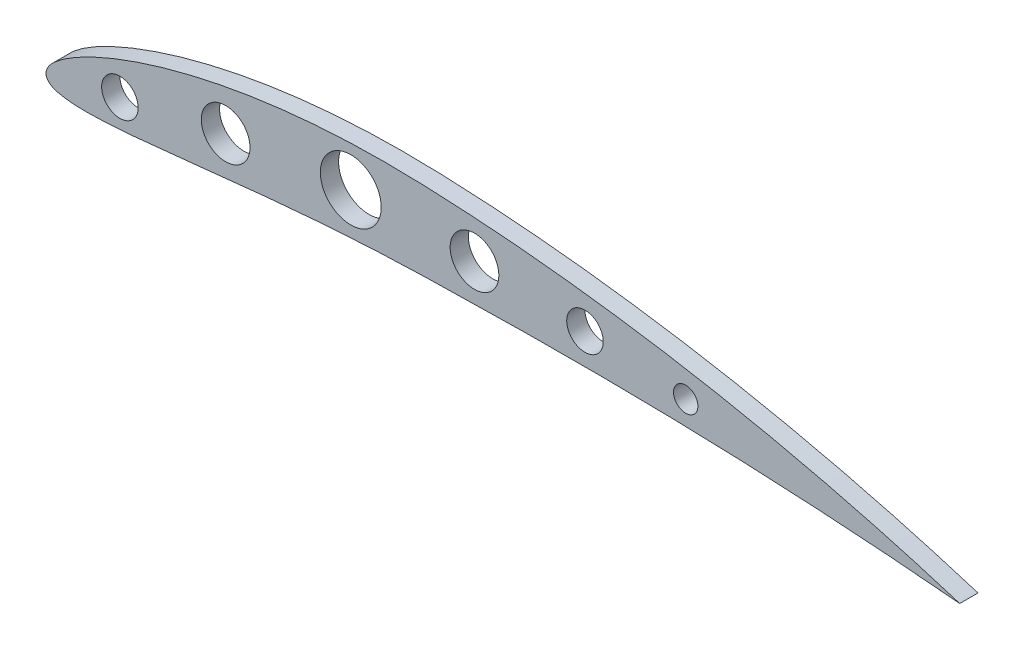
SolidWorks part; units mm, degrees
ref_plane "前基準面" through (0, 0, 0) normal (0, 0, 1) x (1, 0, 0)
ref_plane "上基準面" through (0, 0, 0) normal (0, 1, 0) x (1, 0, 0)
ref_plane "右基準面" through (0, 0, 0) normal (1, 0, 0) x (0, 0, -1)
curve "曲線1"
  spline degree 3 poles (149.1065, 0.1017, 0) (150.2196, -0.0437, 0) (149.135, 0.2489, 0) (148.2582, 0.5567, 0) (146.0923, 1.1965, 0) (143.4195, 1.9978, 0) (139.8974, 3.005, 0) (135.7082, 4.154, 0) (130.8404, 5.4202, 0) (125.3584, 6.7539, 0) (119.317, 8.1207, 0) (112.7765, 9.4732, 0) (105.8082, 10.7736, 0) (98.4853, 11.9821, 0) (90.8867, 13.0635, 0) (83.0963, 13.9879, 0) (75.2009, 14.7297, 0) (67.2867, 15.2583, 0) (59.4021, 15.5949, 0) (51.6307, 15.5985, 0) (44.0772, 15.1999, 0) (36.8788, 14.4542, 0) (30.1283, 13.3973, 0) (23.9108, 12.0837, 0) (18.3003, 10.5813, 0) (13.3638, 8.9553, 0) (9.152, 7.2857, 0) (5.7118, 5.628, 0) (3.0538, 4.0665, 0) (1.2116, 2.6133, 0) (0.0851, 1.3376, 0) (-0.1805, -0.0525, 0) (0.7965, -1.0705, 0) (2.413, -1.5314, 0) (4.6951, -1.8007, 0) (7.6882, -1.8133, 0) (11.3621, -1.6287, 0) (15.68, -1.2602, 0) (20.5924, -0.756, 0) (26.0492, -0.1597, 0) (31.9924, 0.4836, 0) (38.3682, 1.1208, 0) (45.1152, 1.6962, 0) (52.1754, 2.1713, 0) (59.5253, 2.4861, 0) (67.096, 2.6625, 0) (74.8069, 2.8196, 0) (82.5373, 2.8993, 0) (90.2002, 2.9074, 0) (97.7131, 2.8344, 0) (104.994, 2.6857, 0) (111.9628, 2.4672, 0) (118.5419, 2.1942, 0) (124.6567, 1.8797, 0) (130.2345, 1.5456, 0) (135.2162, 1.2065, 0) (139.5235, 0.8875, 0) (143.1607, 0.5942, 0) (145.9334, 0.3654, 0) (148.178, 0.1527, 0) (149.1065, 0.1017, 0) (150.2196, -0.0437, 0) (149.135, 0.2489, 0) knots -0.012269 -0.005489 -0.001366 0 0.001375 0.005484 0.012273 0.021682 0.033581 0.047831 0.064306 0.082777 0.103064 0.124929 0.148149 0.172445 0.197572 0.223269 0.249228 0.275186 0.300901 0.326463 0.351222 0.374906 0.39727 0.418072 0.43708 0.454093 0.46892 0.481392 0.491447 0.499024 0.504294 0.507922 0.51154 0.516781 0.524216 0.533992 0.546034 0.56022 0.576403 0.594371 0.613951 0.634917 0.657089 0.68023 0.704175 0.72909 0.754354 0.779668 0.80476 0.829359 0.853209 0.876041 0.897604 0.917662 0.93597 0.95231 0.966503 0.97835 0.987731 0.994511 0.998634 1 1.001375 1.005484 1.012273 periodic
sketch "草圖1" plane through (0, 0, 0) normal (0, 0, 1) x (1, 0, 0)
  circle A0 centre (50, 8.8348) radius 5
  circle A1 centre (105, 6.5566) radius 2
  circle A2 centre (29.4551, 6.5566) radius 4
  circle A3 centre (70.3168, 8.8348) radius 4
  circle A4 centre (88.4596, 7.9533) radius 3
  circle A5 centre (12.0879, 3.0405) radius 3
  spline S0 degree 3 poles (149.1065, 0.1017) (150.2196, -0.0437) (149.135, 0.2489) (148.2582, 0.5567) (146.0923, 1.1965) (143.4195, 1.9978) (139.8974, 3.005) (135.7082, 4.154) (130.8404, 5.4202) (125.3584, 6.7539) (119.317, 8.1207) (112.7765, 9.4732) (105.8082, 10.7736) (98.4853, 11.9821) (90.8867, 13.0635) (83.0963, 13.9879) (75.2009, 14.7297) (67.2867, 15.2583) (59.4021, 15.5949) (51.6307, 15.5985) (44.0772, 15.1999) (36.8788, 14.4542) (30.1283, 13.3973) (23.9108, 12.0837) (18.3003, 10.5813) (13.3638, 8.9553) (9.152, 7.2857) (5.7118, 5.628) (3.0538, 4.0665) (1.2116, 2.6133) (0.0851, 1.3376) (-0.1805, -0.0525) (0.7965, -1.0705) (2.413, -1.5314) (4.6951, -1.8007) (7.6882, -1.8133) (11.3621, -1.6287) (15.68, -1.2602) (20.5924, -0.756) (26.0492, -0.1597) (31.9924, 0.4836) (38.3682, 1.1208) (45.1152, 1.6962) (52.1754, 2.1713) (59.5253, 2.4861) (67.096, 2.6625) (74.8069, 2.8196) (82.5373, 2.8993) (90.2002, 2.9074) (97.7131, 2.8344) (104.994, 2.6857) (111.9628, 2.4672) (118.5419, 2.1942) (124.6567, 1.8797) (130.2345, 1.5456) (135.2162, 1.2065) (139.5235, 0.8875) (143.1607, 0.5942) (145.9334, 0.3654) (148.178, 0.1527) (149.1065, 0.1017) (150.2196, -0.0437) (149.135, 0.2489) knots -0.012269 -0.005489 -0.001366 0 0.001375 0.005484 0.012273 0.021682 0.033581 0.047831 0.064306 0.082777 0.103064 0.124929 0.148149 0.172445 0.197572 0.223269 0.249228 0.275186 0.300901 0.326463 0.351222 0.374906 0.39727 0.418072 0.43708 0.454093 0.46892 0.481392 0.491447 0.499024 0.504294 0.507922 0.51154 0.516781 0.524216 0.533992 0.546034 0.56022 0.576403 0.594371 0.613951 0.634917 0.657089 0.68023 0.704175 0.72909 0.754354 0.779668 0.80476 0.829359 0.853209 0.876041 0.897604 0.917662 0.93597 0.95231 0.966503 0.97835 0.987731 0.994511 0.998634 1 1.001375 1.005484 1.012273 only from (150, 0) to (150, 0) construction
  spline S1 degree 3 poles (149.1065, 0.1017) (150.2196, -0.0437) (149.135, 0.2489) (148.2582, 0.5567) (146.0923, 1.1965) (143.4195, 1.9978) (139.8974, 3.005) (135.7082, 4.154) (130.8404, 5.4202) (125.3584, 6.7539) (119.317, 8.1207) (112.7765, 9.4732) (105.8082, 10.7736) (98.4853, 11.9821) (90.8867, 13.0635) (83.0963, 13.9879) (75.2009, 14.7297) (67.2867, 15.2583) (59.4021, 15.5949) (51.6307, 15.5985) (44.0772, 15.1999) (36.8788, 14.4542) (30.1283, 13.3973) (23.9108, 12.0837) (18.3003, 10.5813) (13.3638, 8.9553) (9.152, 7.2857) (5.7118, 5.628) (3.0538, 4.0665) (1.2116, 2.6133) (0.0851, 1.3376) (-0.1805, -0.0525) (0.7965, -1.0705) (2.413, -1.5314) (4.6951, -1.8007) (7.6882, -1.8133) (11.3621, -1.6287) (15.68, -1.2602) (20.5924, -0.756) (26.0492, -0.1597) (31.9924, 0.4836) (38.3682, 1.1208) (45.1152, 1.6962) (52.1754, 2.1713) (59.5253, 2.4861) (67.096, 2.6625) (74.8069, 2.8196) (82.5373, 2.8993) (90.2002, 2.9074) (97.7131, 2.8344) (104.994, 2.6857) (111.9628, 2.4672) (118.5419, 2.1942) (124.6567, 1.8797) (130.2345, 1.5456) (135.2162, 1.2065) (139.5235, 0.8875) (143.1607, 0.5942) (145.9334, 0.3654) (148.178, 0.1527) (149.1065, 0.1017) (150.2196, -0.0437) (149.135, 0.2489) knots -0.012269 -0.005489 -0.001366 0 0.001375 0.005484 0.012273 0.021682 0.033581 0.047831 0.064306 0.082777 0.103064 0.124929 0.148149 0.172445 0.197572 0.223269 0.249228 0.275186 0.300901 0.326463 0.351222 0.374906 0.39727 0.418072 0.43708 0.454093 0.46892 0.481392 0.491447 0.499024 0.504294 0.507922 0.51154 0.516781 0.524216 0.533992 0.546034 0.56022 0.576403 0.594371 0.613951 0.634917 0.657089 0.68023 0.704175 0.72909 0.754354 0.779668 0.80476 0.829359 0.853209 0.876041 0.897604 0.917662 0.93597 0.95231 0.966503 0.97835 0.987731 0.994511 0.998634 1 1.001375 1.005484 1.012273 only from (150, 0) to (150, 0)
  point P12 (12.0879, 3.0405)
  point P15 (29.4551, 6.5566)
  point P16 (84.8106, 7.7302)
  point P17 (69.9969, 8.8348)
  point P18 (88.4596, 7.9533)
  point P19 (70.3168, 8.8348)
  dimension "D1" = 10
  dimension "D2" = 4
  dimension "D5" = 8
  dimension "D6" = 8
  dimension "D7" = 6
  dimension "D8" = 6
  dimension "D3" = 50
  dimension "D4" = 105
extrude "填料-伸長1" add sketch "草圖1" along normal blind 3
